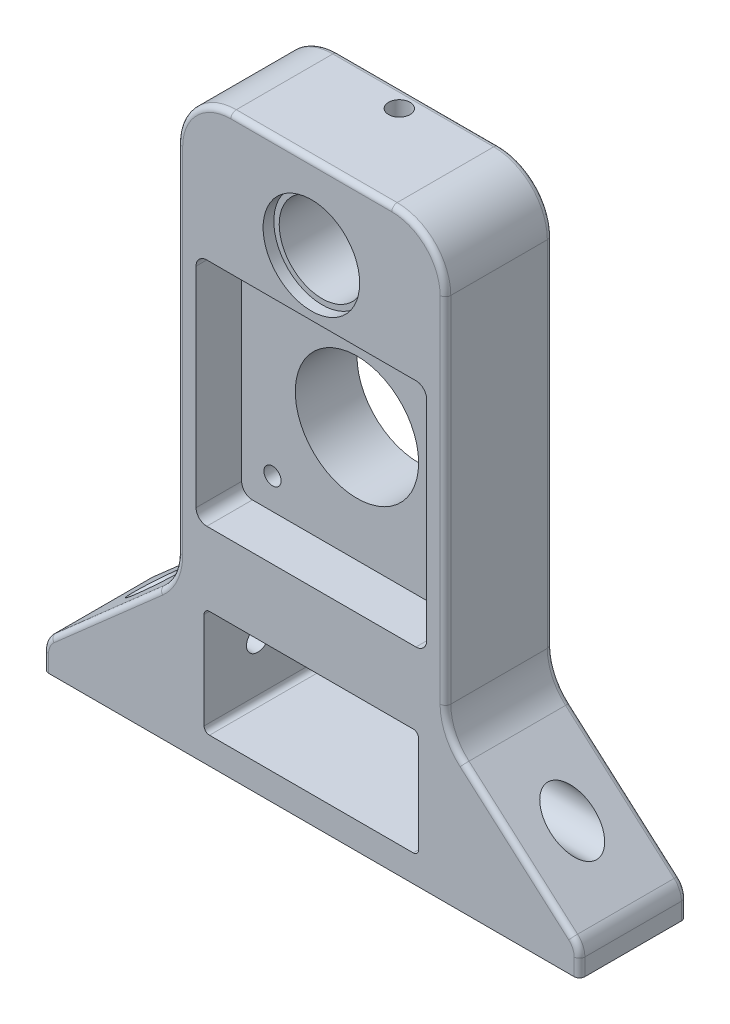
SolidWorks part; units mm, degrees
ref_plane "Front Plane" through (0, 0, 0) normal (0, 0, 1) x (1, 0, 0)
ref_plane "Top Plane" through (0, 0, 0) normal (0, 1, 0) x (1, 0, 0)
ref_plane "Right Plane" through (0, 0, 0) normal (1, 0, 0) x (0, 0, -1)
sketch "Sketch1" plane through (0, 0, 0) normal (0, 0, 1) x (1, 0, 0)
  line L0 (0, 10) -> (0, -10) construction
  line L1 (-19, 10) -> (19, 10)
  line L2 (-20, 9) -> (-20, -9)
  line L3 (-19, -10) -> (19, -10)
  line L4 (20, 9) -> (20, -9)
  line L5 (-20, 10) -> (20, -10) construction
  line L6 (-20, -10) -> (20, 10) construction
  line L7 (-50, -15) -> (50, -15)
  line L8 (-50, -15) -> (-50, -11.8083)
  line L9 (-48.6425, -8.8054) -> (-28.3937, 9.0135)
  line L10 (50, -15) -> (50, -11.8083)
  line L11 (48.6425, -8.8054) -> (28.3937, 9.0135)
  line L14 (-25, 16.5207) -> (-25, 82.5207)
  line L15 (-15, 92.5207) -> (15, 92.5207)
  line L16 (25, 16.5207) -> (25, 82.5207)
  arc A0 (19, 10) -> (20, 9) centre (19, 9) cw
  arc A1 (20, -9) -> (19, -10) centre (19, -9) cw
  arc A2 (-19, -10) -> (-20, -9) centre (-19, -9) cw
  arc A3 (-20, 9) -> (-19, 10) centre (-19, 9) cw
  arc A4 (28.3937, 9.0135) -> (25, 16.5207) centre (35, 16.5207) cw
  arc A5 (-28.3937, 9.0135) -> (-25, 16.5207) centre (-35, 16.5207) ccw
  arc A6 (25, 82.5207) -> (15, 92.5207) centre (15, 82.5207) ccw
  arc A7 (-15, 92.5207) -> (-25, 82.5207) centre (-15, 82.5207) ccw
  arc A8 (50, -11.8083) -> (48.6425, -8.8054) centre (46, -11.8083) ccw
  arc A9 (-50, -11.8083) -> (-48.6425, -8.8054) centre (-46, -11.8083) cw
  point P0 (0, 0)
  point P18 (0, 0)
  point P39 (-25, 92.5207)
  point P40 (50, -10)
  point P43 (-50, -10)
  dimension "D3" = 1
  dimension "D9" = 10
  dimension "D6" = 4
  dimension "D1" = 40
  dimension "D2" = 20
  dimension "D4" = 15
  dimension "D5" = 100
  dimension "D7" = 66
  dimension "D8" = 5
extrude "Boss-Extrude1" add sketch "Sketch1" along normal blind 20
sketch "Sketch4" plane through (0, 0, 20) normal (0, 0, 1) x (1, 0, 0)
  line L0 (0, 92.5207) -> (0, -15) construction
  line L1 (-19.5, 66.5) -> (19.5, 66.5)
  line L2 (-21.5, 64.5) -> (-21.5, 25.5)
  line L3 (-19.5, 23.5) -> (19.5, 23.5)
  line L4 (21.5, 64.5) -> (21.5, 25.5)
  line L5 (-21.5, 66.5) -> (21.5, 23.5) construction
  line L6 (-21.5, 23.5) -> (21.5, 66.5) construction
  line L7 (15, 92.5207) -> (-15, 92.5207) construction
  line L8 (-50, -15) -> (50, -15) construction
  arc A0 (-21.5, 25.5) -> (-19.5, 23.5) centre (-19.5, 25.5) ccw
  arc A1 (19.5, 23.5) -> (21.5, 25.5) centre (19.5, 25.5) ccw
  arc A2 (19.5, 66.5) -> (21.5, 64.5) centre (19.5, 64.5) cw
  arc A3 (-19.5, 66.5) -> (-21.5, 64.5) centre (-19.5, 64.5) ccw
  point P0 (0, 45)
  dimension "D3" = 2
  dimension "D1" = 43
  dimension "D2" = 43
  dimension "D4" = 60
extrude "Cut-Extrude3" cut sketch "Sketch4" against normal blind 8.5
sketch "Sketch5" plane through (0, 0, 11.5) normal (0, 0, 1) x (1, 0, 0)
  line L0 (0, 66.5) -> (0, 23.5) construction
  line L1 (-15.75, 29.25) -> (15.75, 29.25) construction
  line L2 (-15.75, 29.25) -> (-15.75, 60.75) construction
  line L3 (-15.75, 60.75) -> (15.75, 60.75) construction
  line L4 (15.75, 29.25) -> (15.75, 60.75) construction
  line L5 (-15.75, 29.25) -> (15.75, 60.75) construction
  line L6 (-15.75, 60.75) -> (15.75, 29.25) construction
  line L7 (19.5, 66.5) -> (-19.5, 66.5) construction
  line L8 (-19.5, 23.5) -> (19.5, 23.5) construction
  circle A0 centre (0, 45) radius 11.5
  circle A1 centre (-15.75, 60.75) radius 1.6
  circle A2 centre (15.75, 60.75) radius 1.6
  circle A3 centre (-15.75, 29.25) radius 1.6
  circle A4 centre (15.75, 29.25) radius 1.6
  dimension "D1" = 31.5
  dimension "D2" = 31.5
extrude "Cut-Extrude4" cut sketch "Sketch5" against normal up to next
sketch "Sketch6" plane through (0, 0, 0) normal (0, 0, -1) x (-1, 0, 0)
  line L0 (0, 45) -> (0, 77) construction
  circle A0 centre (0, 77) radius 8
  dimension "D1" = 32
extrude "Cut-Extrude5" cut sketch "Sketch6" against normal up to next
sketch "Sketch7" plane through (0, 0, 0) normal (0, 0, -1) x (-1, 0, 0)
  circle A1 centre (-15.75, 60.75) radius 3
  circle A2 centre (15.75, 60.75) radius 3
  circle A3 centre (15.75, 29.25) radius 3
  circle A4 centre (-15.75, 29.25) radius 3
extrude "Cut-Extrude6" cut sketch "Sketch7" against normal blind 4
sketch "Sketch8" plane through (0, 0, 0) normal (0, 0, -1) x (-1, 0, 0)
  circle A0 centre (0, 77) radius 9
extrude "Cut-Extrude7" cut sketch "Sketch8" against normal blind 6
sketch "Sketch9" plane through (0, 0, 20) normal (0, 0, 1) x (1, 0, 0)
  circle A0 centre (0, 77) radius 9
extrude "Cut-Extrude8" cut sketch "Sketch9" against normal blind 2
sketch "Sketch10" plane through (0, 92.5207, 0) normal (0, 1, 0) x (1, 0, 0)
  circle A0 centre (0, -3.6) radius 2
  dimension "D1" = 3.6
extrude "Cut-Extrude9" cut sketch "Sketch10" against normal up to next
fillet "Fillet1" radius 1 26 edges at (50, -13.4041, 20) (49.6449, -10.1605, 20) (38.5181, 0.1041, 20) (25.8878, 12.4014, 20) (-50, -13.4041, 20) (-49.6449, -10.1605, 20) (-38.5181, 0.1041, 20) (-25.8878, 12.4014, 20) (-25, 49.5207, 20) (-22.0711, 89.5917, 20) (0, 92.5207, 20) (22.0711, 89.5917, 20) (50, -13.4041, 0) (49.6449, -10.1605, 0) (38.5181, 0.1041, 0) (25.8878, 12.4014, 0) (-50, -13.4041, 0) (-49.6449, -10.1605, 0) (-38.5181, 0.1041, 0) (-25.8878, 12.4014, 0) (-25, 49.5207, 0) (-22.0711, 89.5917, 0) (0, 92.5207, 0) (22.0711, 89.5917, 0) (25, 49.5207, 20) (25, 49.5207, 0)
sketch "Sketch11" plane through (-20, 0, 0) normal (1, 0, 0) x (0, 0, -1)
  circle A0 centre (-10, 0) radius 2.1
extrude "Cut-Extrude10" cut sketch "Sketch11" against normal up to next and the other way up to next
sketch "Sketch12" plane through (-20, 0, 0) normal (1, 0, 0) x (0, 0, -1)
  circle A0 centre (-10, 0) radius 4
extrude "Cut-Extrude11" cut sketch "Sketch12" against normal up to next from offset 8 offset against normal yes
sketch "Sketch13" plane through (20, 0, 0) normal (-1, 0, 0) x (0, 0, 1)
  circle A0 centre (10, 0) radius 4
extrude "Cut-Extrude12" cut sketch "Sketch13" against normal up to next from offset 8
